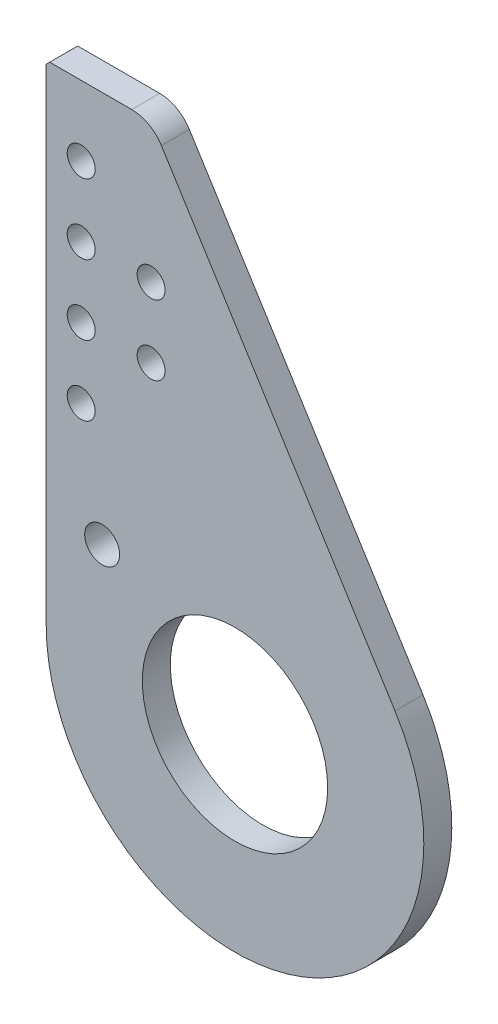
SolidWorks part; units mm, degrees
material "6061 合金"
ref_plane "前视基准面" through (0, 0, 0) normal (0, 0, 1) x (1, 0, 0)
ref_plane "上视基准面" through (0, 0, 0) normal (0, 1, 0) x (1, 0, 0)
ref_plane "右视基准面" through (0, 0, 0) normal (1, 0, 0) x (0, 0, -1)
sketch "草图1" plane through (0, 0, 0) normal (0, 0, 1) x (1, 0, 0)
  line L0 (0, 0) -> (0, 70) construction
  line L1 (-27, 0) -> (-27, 70)
  line L2 (-27, 70) -> (-12, 70)
  line L3 (-12, 70) -> (22.8794, 14.3365)
  line L4 (0, 0) -> (0, 35) construction
  line L5 (-22, 70) -> (-22, 60) construction
  line L6 (-22, 60) -> (-22, 50) construction
  line L7 (-22, 50) -> (-22, 30) construction
  line L8 (-22, 30) -> (-22, 20) construction
  line L12 (-22, 30) -> (-22, 14) construction
  line L13 (-22, 14) -> (-19, 14) construction
  arc A0 (-27, 0) -> (22.8794, 14.3365) centre (0, 0) ccw
  circle A1 centre (0, 0) radius 22.5 construction
  circle A6 centre (-22, 60) radius 2
  circle A7 centre (-22, 50) radius 2
  circle A8 centre (-22, 30) radius 2
  circle A13 centre (-22, 40) radius 2
  circle A16 centre (-12, 50) radius 2
  circle A24 centre (0, 0) radius 13.25
  circle A25 centre (-12, 40) radius 2
  circle A28 centre (-19, 14) radius 2.5
  point P19 (0, 0)
  point P46 (0, 0)
  dimension "D1" = 10
  dimension "D4" = 27
  dimension "D2" = 10
  dimension "D3" = 70
  dimension "D5" = 10
  dimension "D6" = 20
  dimension "D7" = 10
  dimension "D9" = 5
extrude "凸台-拉伸1" add sketch "草图1" along normal blind 4
fillet "圆角1" radius 5 1 edges at (-12, 70, 2)
chamfer "倒角1" distance 0.5 angle 45 1 edges at (-27, 70, 2)
